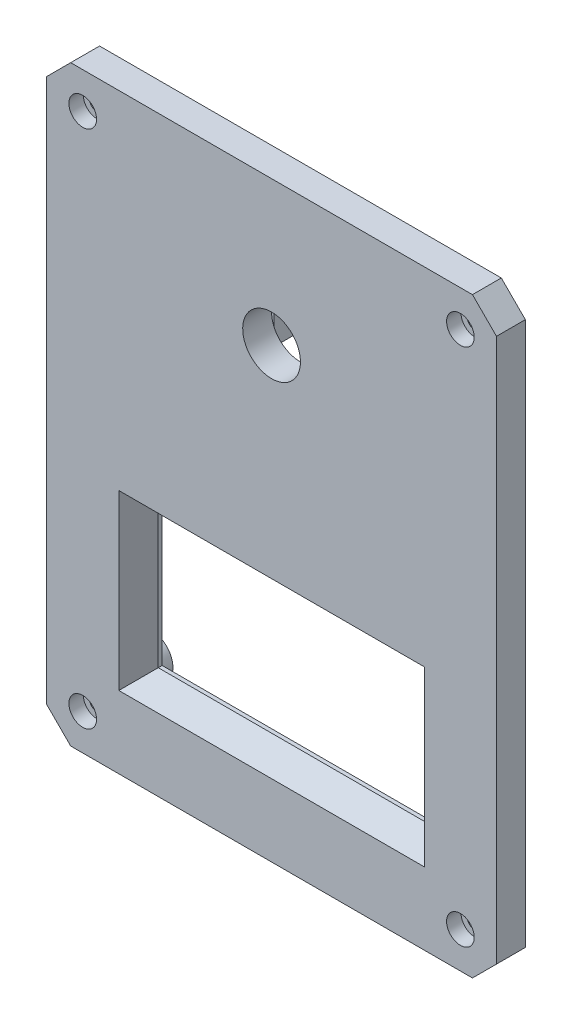
SolidWorks part; units mm, degrees
ref_plane "Front Plane" through (0, 0, 0) normal (0, 0, 1) x (1, 0, 0)
ref_plane "Top Plane" through (0, 0, 0) normal (0, 1, 0) x (1, 0, 0)
ref_plane "Right Plane" through (0, 0, 0) normal (1, 0, 0) x (0, 0, -1)
sketch "Sketch1" plane through (0, 0, 0) normal (0, 0, 1) x (1, 0, 0)
  line L0 (0, 89.3483) -> (0, -89.3483) construction
  line L1 (-65.6205, 89.3483) -> (65.6205, 89.3483) construction
  line L2 (-65.6205, 89.3483) -> (-65.6205, -89.3483) construction
  line L3 (-65.6205, -89.3483) -> (65.6205, -89.3483) construction
  line L4 (65.6205, 89.3483) -> (65.6205, -89.3483) construction
  line L5 (-65.6205, 0) -> (65.6205, 0) construction
  line L6 (28.75, -15) -> (-28.75, 15) construction
  line L7 (-28.75, 15) -> (28.75, 15)
  line L8 (-28.75, 15) -> (-28.75, -15)
  line L9 (-28.75, -15) -> (28.75, -15)
  line L10 (28.75, 15) -> (28.75, -15)
  line L12 (-46.75, -33) -> (46.75, -33)
  line L13 (-46.75, -33) -> (-46.75, 90)
  line L14 (-46.75, 90) -> (46.75, 90)
  line L15 (46.75, -33) -> (46.75, 90)
  circle A0 centre (0, 60) radius 6
  dimension "D3" = 12
  dimension "D1" = 57.5
  dimension "D2" = 30
  dimension "D4" = 60
  dimension "D5" = 30
  dimension "D6" = 18
  dimension "D7" = 18
  dimension "D8" = 18
extrude "Boss-Extrude1" add sketch "Sketch1" along normal blind 6
sketch "Sketch2" plane through (0, 0, 0) normal (0, 0, -1) x (-1, 0, 0)
  line L0 (0, 0) -> (0, -17.25) construction
  line L1 (34, -17.25) -> (-34, -17.25) construction
  line L2 (34, -17.25) -> (34, 21.75) construction
  line L3 (34, 21.75) -> (-34, 21.75) construction
  line L4 (-34, -17.25) -> (-34, 21.75) construction
  line L6 (0, 0) -> (0, 90) construction
  line L8 (0, 60) -> (8, 60) construction
  line L9 (8, 60) -> (8, 51.6) construction
  line L10 (5.5, 47.6) -> (5.5, 72.4)
  line L11 (5.5, 72.4) -> (13.5, 72.4)
  line L12 (13.5, 72.4) -> (13.5, 47.6)
  line L13 (13.5, 47.6) -> (5.5, 47.6)
  line L15 (-5.5, 54) -> (-10.5, 54)
  line L16 (-5.5, 54) -> (-5.5, 66)
  line L17 (-5.5, 66) -> (-10.5, 66)
  line L18 (-10.5, 54) -> (-10.5, 66)
  line L20 (-46.75, 90) -> (46.75, 90) construction
  circle A0 centre (34, -17.25) radius 2.1
  circle A1 centre (-34, -17.25) radius 2.1
  circle A2 centre (-34, 21.75) radius 2.1
  circle A3 centre (34, 21.75) radius 2.1
  circle A4 centre (34, -17.25) radius 4.5
  circle A5 centre (34, 21.75) radius 4.5
  circle A6 centre (-34, -17.25) radius 4.5
  circle A7 centre (-34, 21.75) radius 4.5
  circle A8 centre (8, 51.6) radius 2.1
  circle A9 centre (8, 68.4) radius 2.1
  dimension "D1" = 4.2
  dimension "D2" = 4.2
  dimension "D3" = 4.2
  dimension "D4" = 4.2
  dimension "D8" = 9
  dimension "D9" = 9
  dimension "D10" = 4.2
  dimension "D17" = 11
  dimension "D5" = 68
  dimension "D6" = 39
  dimension "D7" = 2.25
  dimension "D11" = 8.4
  dimension "D12" = 8
  dimension "D13" = 2.5
  dimension "D14" = 8
  dimension "D15" = 4
  dimension "D16" = 4
  dimension "D18" = 5
  dimension "D19" = 12
  dimension "D20" = 6
extrude "Boss-Extrude2" add sketch "Sketch2" along normal blind 3 contours A5 A3 | A6 A1 | A4 A0 | A7 A2
chamfer "Chamfer2" distance 5 angle 45 4 edges at (46.75, -33, 3) (-46.75, -33, 3) (-46.75, 90, 3) (46.75, 90, 3)
sketch "Sketch5" plane through (0, 0, 6) normal (0, 0, 1) x (1, 0, 0)
  line L0 (0, 0) -> (0, 79.1201) construction
  line L1 (46.75, -25.5) -> (39.25, -25.5) construction
  line L2 (46.75, -28) -> (46.75, 85) construction
  line L3 (39.25, -25.5) -> (39.25, -33) construction
  line L4 (-41.75, -33) -> (41.75, -33) construction
  line L5 (39.25, 90) -> (39.25, 82.5) construction
  line L6 (41.75, 90) -> (-41.75, 90) construction
  line L7 (39.25, 82.5) -> (46.75, 82.5) construction
  circle A0 centre (39.25, -25.5) radius 2.875
  circle A1 centre (39.25, 82.5) radius 2.875
  circle A2 centre (-39.25, -25.5) radius 2.875
  circle A3 centre (-39.25, 82.5) radius 2.875
  dimension "D1" = 5.75
  dimension "D4" = 5.75
  dimension "D2" = 7.5
  dimension "D3" = 7.5
  dimension "D5" = 7.5
  dimension "D6" = 7.5
extrude "Cut-Extrude2" cut sketch "Sketch5" against normal blind 3
sketch "Sketch6" plane through (0, 0, 3) normal (0, 0, 1) x (1, 0, 0)
  circle A0 centre (39.25, -25.5) radius 1.625
  circle A1 centre (-39.25, -25.5) radius 1.625
  circle A2 centre (-39.25, 82.5) radius 1.625
  circle A3 centre (39.25, 82.5) radius 1.625
  dimension "D1" = 3.25
  dimension "D2" = 3.25
  dimension "D3" = 3.25
  dimension "D4" = 3.25
extrude "Cut-Extrude3" cut sketch "Sketch6" against normal blind 23
sketch "Sketch7" plane through (0, 0, 0) normal (0, 0, 1) x (1, 0, 0)
  line L0 (0, 0) -> (0, -17.25) construction
  line L1 (34, -17.25) -> (-34, -17.25) construction
  line L2 (34, -17.25) -> (34, 21.75) construction
  line L3 (34, 21.75) -> (-34, 21.75) construction
  line L4 (-34, -17.25) -> (-34, 21.75) construction
  line L6 (0, 0) -> (0, 90) construction
  line L8 (0, 60) -> (8, 60) construction
  line L9 (8, 60) -> (8, 51.6) construction
  line L10 (5.5, 47.6) -> (5.5, 72.4)
  line L11 (5.5, 72.4) -> (13.5, 72.4)
  line L12 (13.5, 72.4) -> (13.5, 47.6)
  line L13 (13.5, 47.6) -> (5.5, 47.6)
  line L15 (-5.5, 54) -> (-10.5, 54)
  line L16 (-5.5, 54) -> (-5.5, 66)
  line L17 (-5.5, 66) -> (-10.5, 66)
  line L18 (-10.5, 54) -> (-10.5, 66)
  circle A0 centre (34, -17.25) radius 2.1
  circle A1 centre (-34, -17.25) radius 2.1
  circle A2 centre (-34, 21.75) radius 2.1
  circle A3 centre (34, 21.75) radius 2.1
  circle A4 centre (34, -17.25) radius 4.5
  circle A5 centre (34, 21.75) radius 4.5
  circle A6 centre (-34, -17.25) radius 4.5
  circle A7 centre (-34, 21.75) radius 4.5
  circle A8 centre (8, 51.6) radius 2.1
  circle A9 centre (8, 68.4) radius 2.1
  dimension "D1" = 4.2
  dimension "D2" = 4.2
  dimension "D3" = 4.2
  dimension "D4" = 4.2
  dimension "D8" = 9
  dimension "D9" = 9
  dimension "D10" = 4.2
  dimension "D17" = 11
  dimension "D5" = 68
  dimension "D6" = 39
  dimension "D11" = 8.4
  dimension "D12" = 8
  dimension "D13" = 2.5
  dimension "D14" = 8
  dimension "D15" = 4
  dimension "D16" = 4
  dimension "D18" = 5
  dimension "D19" = 12
  dimension "D20" = 6
extrude "Boss-Extrude3" add sketch "Sketch7" against normal blind 6 contours L18 L15 L16 L17 | L13 L12 L11 L10 A8 A9
chamfer "Chamfer3" distance 3 angle 60 4 edges at (0, 15, 6) (28.75, 0, 6) (0, -15, 6) (-28.75, 0, 6)
sketch "Sketch9" plane through (0, 0, 0) normal (0, 0, -1) x (-1, 0, 0)
  line L0 (30, 45) -> (30, 75) construction
  line L1 (0, 60) -> (30, 60) construction
  line L2 (0, 60) -> (0, 62.8351) construction
  circle A0 centre (30, 75) radius 2.1
  circle A1 centre (30, 45) radius 2.1
  circle A2 centre (-30, 45) radius 2.1
  circle A3 centre (-30, 75) radius 2.1
  dimension "D1" = 4.2
  dimension "D2" = 4.2
  dimension "D3" = 30
  dimension "D4" = 30
extrude "Cut-Extrude5" cut sketch "Sketch9" against normal blind 3
